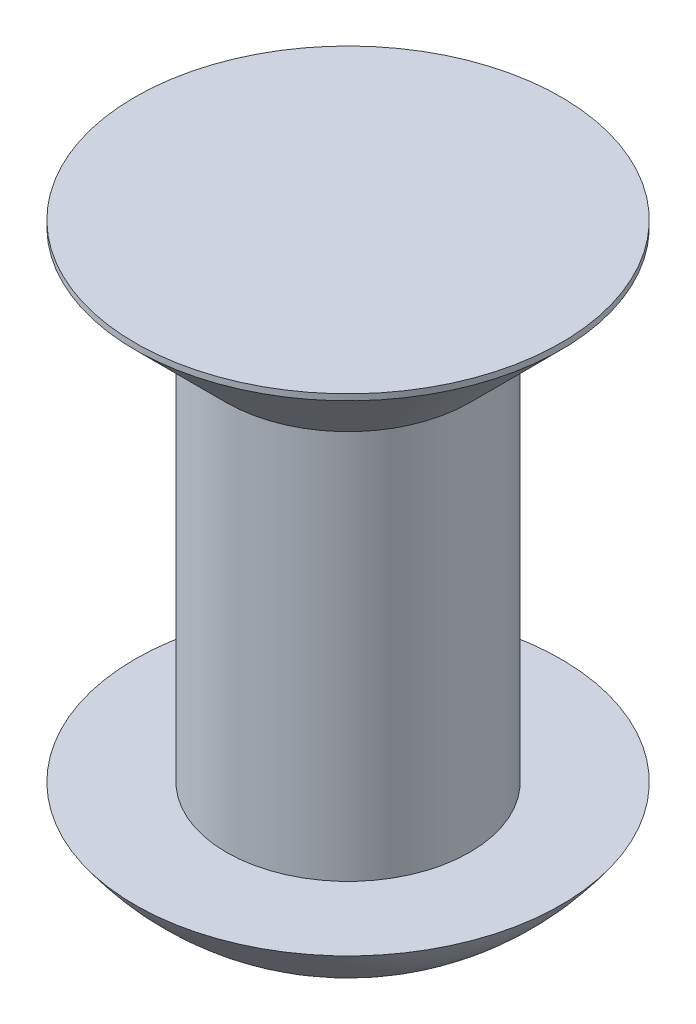
SolidWorks part; units mm, degrees
ref_plane "Спереди" through (0, 0, 0) normal (0, 0, 1) x (1, 0, 0)
ref_plane "Сверху" through (0, 0, 0) normal (0, 1, 0) x (1, 0, 0)
ref_plane "Справа" through (0, 0, 0) normal (1, 0, 0) x (0, 0, -1)
sketch "Эскиз1" plane through (0, 0, 0) normal (0, 0, 1) x (1, 0, 0)
  line L0 (0, 8) -> (0, -1.8317) construction
  line L1 (2, 0) -> (3.5, 0)
  line L2 (2, 0) -> (2, 6.4)
  line L3 (2, 6.4) -> (3.5, 7.9)
  line L4 (3.5, 7.9) -> (3.5, 8)
  line L5 (3.5, 8) -> (0, 8)
  line L6 (0, -1.8317) -> (0, 8)
  arc A0 (3.5, 0) -> (0, -1.8317) centre (0.0009, 2.4263) cw
  point P11 (2, 0)
  dimension "dm" = 4
  dimension "L" = 6.4
  dimension "D" = 7
  dimension "D4" = 45
revolve "Основание-Повернуть" add sketch "Эскиз1" angle 360 about L0
